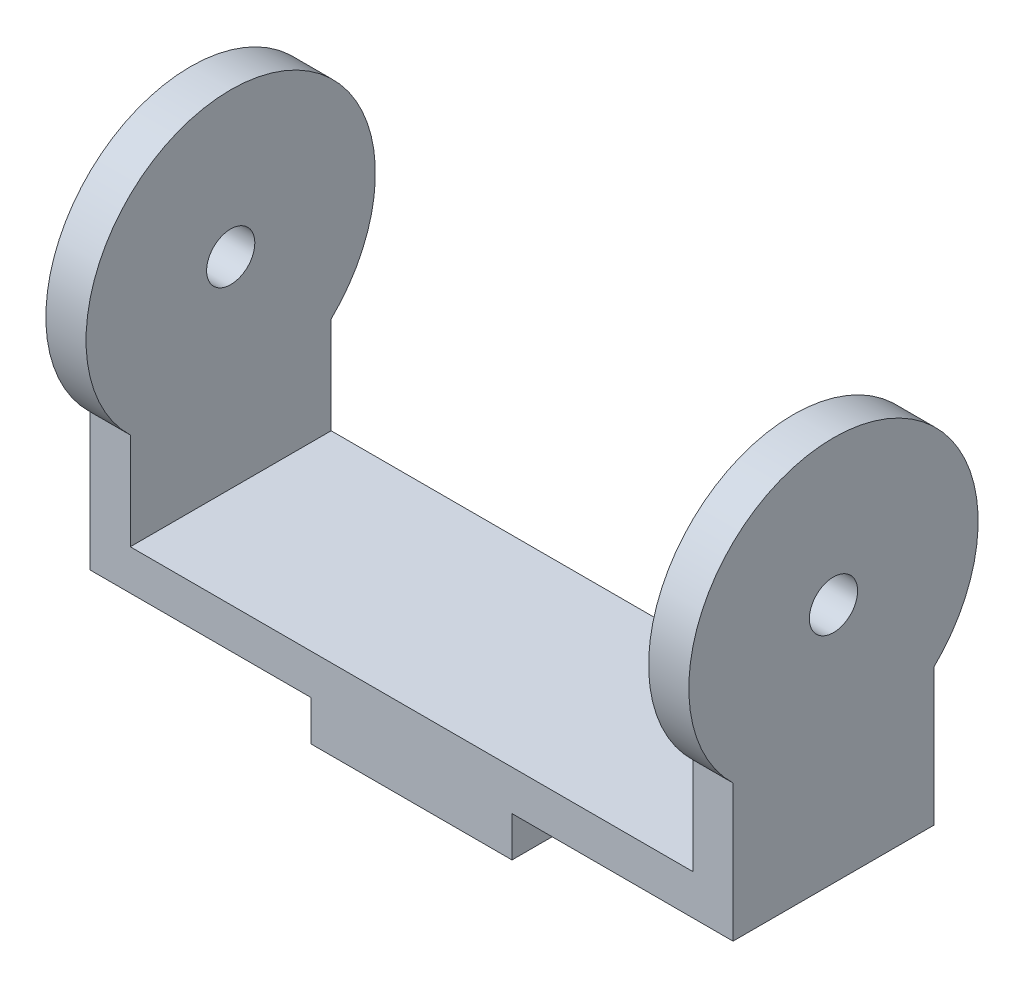
SolidWorks part; units mm, degrees
material "1060 Alloy"
ref_plane "Front Plane" through (0, 0, 0) normal (0, 0, 1) x (1, 0, 0)
ref_plane "Top Plane" through (0, 0, 0) normal (0, 1, 0) x (1, 0, 0)
ref_plane "Right Plane" through (0, 0, 0) normal (1, 0, 0) x (0, 0, -1)
sketch "Sketch1" plane through (0, 0, 0) normal (0, 1, 0) x (1, 0, 0)
  line L1 (0, 12.5) -> (40, 12.5)
  line L2 (0, 12.5) -> (0, -12.5)
  line L3 (0, -12.5) -> (40, -12.5)
  line L4 (40, 12.5) -> (40, -12.5)
  dimension "D1" = 25
  dimension "D2" = 40
  dimension "D3" = 0
extrude "Boss-Extrude1" add sketch "Sketch1" along normal blind 5
sketch "Sketch6" plane through (40, 0, 0) normal (1, 0, 0) x (0, 0, -1)
  line L0 (-12.5, 17.0482) -> (-12.5, 5)
  line L1 (-12.5, 5) -> (12.5, 5)
  line L2 (12.5, 5) -> (12.5, 17.0482)
  circle A0 centre (0, 30) radius 18
  circle A1 centre (0, 30) radius 3
  arc A2 (-12.5, 17.0482) -> (12.5, 17.0482) centre (0, 30) ccw
  line M3 (12.5, 5) -> (-12.5, 5)
  dimension "D1" = 30
extrude "Boss-Extrude4" add sketch "Sketch6" against normal blind 5 contours A0 A1 | A0 L0 L2 M3
mirror "Mirror2" about plane through (0, 5, -12.5) normal (1, 0, 0) of "Boss-Extrude4", "Boss-Extrude1"
sketch "Sketch7" plane through (0, 0, 0) normal (0, -1, 0) x (1, 0, 0)
  line L0 (40, -12.5) -> (-40, -12.5) construction
  line L1 (-12.5, 12.5) -> (12.5, 12.5)
  line L2 (-12.5, 12.5) -> (-12.5, -12.5)
  line L3 (-12.5, -12.5) -> (12.5, -12.5)
  line L4 (12.5, 12.5) -> (12.5, -12.5)
  line L5 (-12.5, 12.5) -> (12.5, -12.5) construction
  line L6 (-12.5, -12.5) -> (12.5, 12.5) construction
  line L7 (40, 12.5) -> (40, -12.5) construction
  point P0 (0, 0)
  dimension "D1" = 25
  dimension "D2" = 25
  dimension "D3" = 27.5
extrude "Boss-Extrude5" add sketch "Sketch7" along normal blind 5
